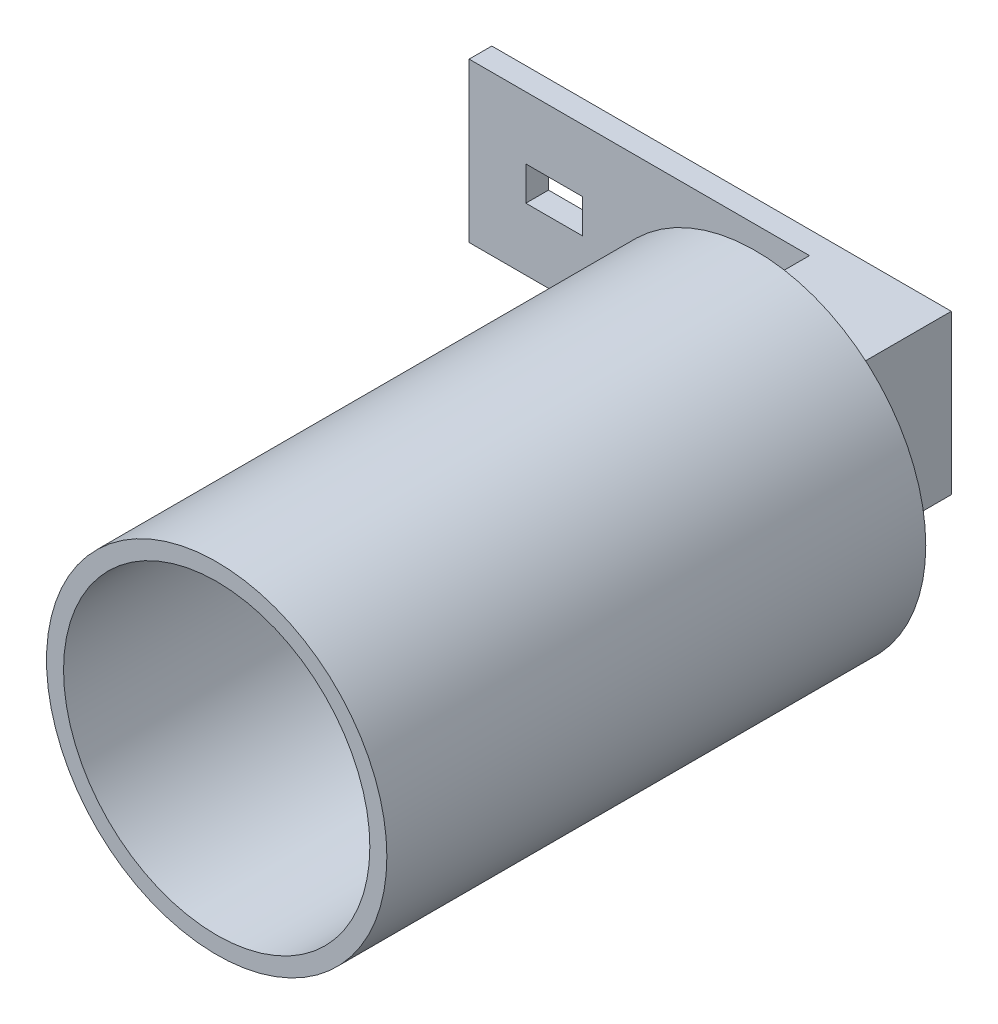
SolidWorks part; units mm, degrees
ref_plane "Plan de face" through (0, 0, 0) normal (0, 0, 1) x (1, 0, 0)
ref_plane "Plan de dessus" through (0, 0, 0) normal (0, 1, 0) x (1, 0, 0)
ref_plane "Plan de droite" through (0, 0, 0) normal (1, 0, 0) x (0, 0, -1)
sketch "Esquisse1" plane through (0, 0, 0) normal (0, 0, 1) x (1, 0, 0)
  circle A0 centre (0, 0) radius 30
  dimension "D1" = 60
extrude "Boss.-Extru.1" add sketch "Esquisse1" along normal blind 95 contours A0
sketch "Esquisse2" plane through (0, 0, 95) normal (0, 0, 1) x (1, 0, 0)
  circle A0 centre (0, 0) radius 27
  circle A1 centre (0, 0) radius 30 construction
  dimension "D1" = 3
extrude "Enlèv. mat.-Extru.1" cut sketch "Esquisse2" against normal blind 80 contours A0
sketch "Esquisse3" plane through (0, 0, 0) normal (0, 0, -1) x (-1, 0, 0)
  line L1 (-10.5, -14) -> (10.5, -14)
  line L2 (-10.5, -14) -> (-10.5, 14)
  line L3 (-10.5, 14) -> (10.5, 14)
  line L4 (10.5, -14) -> (10.5, 14)
  line L5 (-10.5, -14) -> (10.5, 14) construction
  line L6 (-10.5, 14) -> (10.5, -14) construction
  point P0 (0, 0)
  dimension "D1" = 28
  dimension "D2" = 21
extrude "Boss.-Extru.2" add sketch "Esquisse3" along normal blind 24
sketch "Esquisse4" plane through (-10.5, 0, 0) normal (-1, 0, 0) x (0, 0, 1)
  line L0 (0, -14) -> (0, 14) construction
  line L1 (-24, 14) -> (-20, 14)
  line L2 (-24, 14) -> (-24, -14)
  line L3 (-24, -14) -> (-20, -14)
  line L4 (-20, 14) -> (-20, -14)
  line L5 (-24, 14) -> (-20, -14) construction
  line L6 (-24, -14) -> (-20, 14) construction
  line L7 (-24, 14) -> (0, 14) construction
  line L8 (-24, -14) -> (0, -14) construction
  point P0 (-22, 0)
  dimension "D1" = 20
  dimension "D2" = 4
  dimension "D3" = 0
  dimension "D4" = 0
extrude "Boss.-Extru.3" add sketch "Esquisse4" along normal blind 60
sketch "Esquisse5" plane through (0, 0, -24) normal (0, 0, -1) x (-1, 0, 0)
  line L0 (-10.5, -14) -> (70.5, -14) construction
  line L1 (50.5, -3) -> (60.5, -3)
  line L2 (50.5, -3) -> (50.5, 3)
  line L3 (50.5, 3) -> (60.5, 3)
  line L4 (60.5, -3) -> (60.5, 3)
  line L5 (50.5, -3) -> (60.5, 3) construction
  line L6 (50.5, 3) -> (60.5, -3) construction
  line L8 (70.5, 14) -> (70.5, -14) construction
  point P0 (55.5, 0)
  dimension "D1" = 6
  dimension "D2" = 10
  dimension "D3" = 11
  dimension "D4" = 10
extrude "Enlèv. mat.-Extru.2" cut sketch "Esquisse5" against normal up to next
equation "\"taille\"= 3mm"
